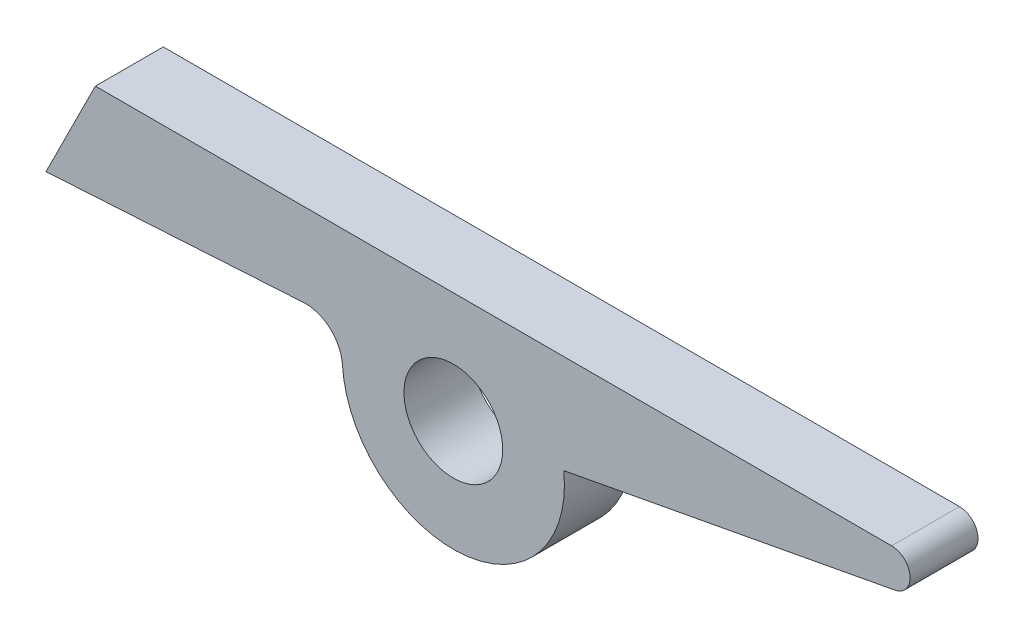
SolidWorks part; units mm, degrees
ref_plane "Front Plane" through (0, 0, 0) normal (0, 0, 1) x (1, 0, 0)
ref_plane "Top Plane" through (0, 0, 0) normal (0, 1, 0) x (1, 0, 0)
ref_plane "Right Plane" through (0, 0, 0) normal (1, 0, 0) x (0, 0, -1)
sketch "Sketch1" plane through (0, 0, 0) normal (0, 0, 1) x (1, 0, 0)
  line L0 (-11.9772, 2.26) -> (-32.9972, 1)
  line L1 (-32.9972, 1) -> (-28.9972, 9)
  line L2 (-28.9972, 9) -> (35.5028, 9)
  line L3 (-32.9972, 8.26) -> (-32.9972, -0.74) construction
  line L4 (-32.9972, -0.74) -> (-11.9772, -0.74) construction
  line L5 (0, 0) -> (-28.3404, 0) construction
  line L7 (-11.9772, -0.74) -> (-11.9772, 2.26) construction
  line L8 (8.94, 9) -> (8.94, 1) construction
  line L9 (8.94, 1) -> (35.7789, 6.0256)
  circle A0 centre (0, 0) radius 4
  arc A1 (-9, 0) -> (8.94, 1.0375) centre (0, 0) ccw
  circle A2 centre (-11.9772, -0.74) radius 3
  arc A3 (35.5028, 9) -> (35.7789, 6.0256) centre (35.5028, 7.5) cw
  point P15 (-9, 0)
  point P16 (-9, 0)
  point P21 (0, 0)
  dimension "D1" = 8
  dimension "D2" = 18
  dimension "D8" = 6
  dimension "D12" = 1.5
  dimension "D3" = 64.5
  dimension "D4" = 4
  dimension "D5" = 9
  dimension "D6" = 8
  dimension "D7" = 21.02
  dimension "D9" = 1.74
  dimension "D10" = 8
  dimension "D11" = 8.94
  dimension "D13" = 8.94
extrude "Boss-Extrude1" add sketch "Sketch1" along normal blind 5.5
